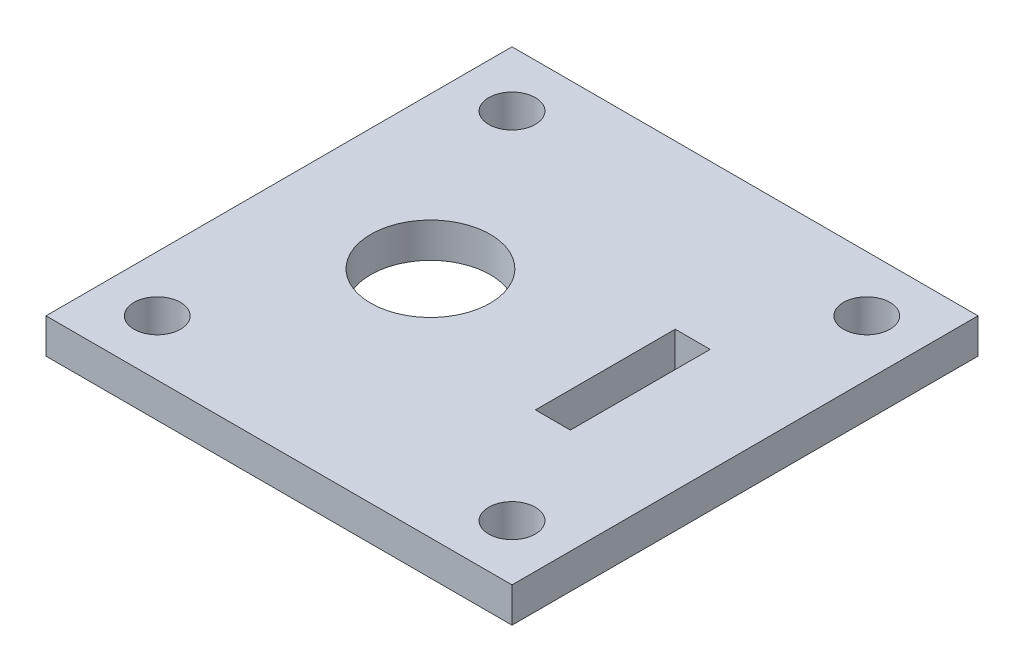
SolidWorks part; units mm, degrees
ref_plane "前视基准面" through (0, 0, 0) normal (0, 0, 1) x (1, 0, 0)
ref_plane "上视基准面" through (0, 0, 0) normal (0, 1, 0) x (1, 0, 0)
ref_plane "右视基准面" through (0, 0, 0) normal (1, 0, 0) x (0, 0, -1)
sketch "草图2" plane through (0, 0, 0) normal (0, 1, 0) x (1, 0, 0)
  line L0 (0, 0) -> (31.047, 0) construction
  line L1 (-9.75, -9.75) -> (9.75, -9.75)
  line L2 (-9.75, -9.75) -> (-9.75, 9.75)
  line L3 (-9.75, 9.75) -> (9.75, 9.75)
  line L4 (9.75, -9.75) -> (9.75, 9.75)
  line L5 (-9.75, -9.75) -> (9.75, 9.75) construction
  line L6 (-9.75, 9.75) -> (9.75, -9.75) construction
  line L7 (-20, -20) -> (20, -20)
  line L8 (-20, -20) -> (-20, 20)
  line L9 (-20, 20) -> (20, 20)
  line L10 (20, -20) -> (20, 20)
  line L11 (-20, -20) -> (20, 20) construction
  line L12 (-20, 20) -> (20, -20) construction
  line L13 (0, 0) -> (0, 17.7315) construction
  circle A0 centre (15.2248, 15.2248) radius 2
  circle A1 centre (-15.2248, -15.2248) radius 2
  circle A2 centre (15.2248, -15.2248) radius 2
  circle A3 centre (-15.2248, 15.2248) radius 2
  point P0 (0, 0)
  point P6 (0, 0)
  dimension "D5" = 4
  dimension "D1" = 19.5
  dimension "D2" = 19.5
  dimension "D3" = 40
  dimension "D4" = 40
  dimension "D6" = 21.5311
extrude "凸台-拉伸2" add sketch "草图2" along normal blind 3 contours L8 L9 L10 L7
sketch "草图3" plane through (0, 0, 0) normal (0, 1, 0) x (1, 0, 0)
  line L7 (8, 6.0116) -> (11, 6.0116)
  line L8 (8, 6.0116) -> (8, -5.9884)
  line L9 (8, -5.9884) -> (11, -5.9884)
  line L10 (11, 6.0116) -> (11, -5.9884)
  circle A0 centre (-15.2248, -15.2248) radius 2 construction
  circle A1 centre (15.2248, -15.2248) radius 2 construction
  circle A2 centre (15.2248, 15.2248) radius 2 construction
  circle A3 centre (-15.2248, 15.2248) radius 2 construction
  circle A4 centre (-15.2248, -15.2248) radius 2
  circle A5 centre (15.2248, -15.2248) radius 2
  circle A6 centre (15.2248, 15.2248) radius 2
  circle A7 centre (-15.2248, 15.2248) radius 2
  circle A8 centre (-7, 0) radius 5.125
  point P27 (8, 0.0116)
  dimension "D1" = 10.25
  dimension "D2" = 8
  dimension "D5" = 12
  dimension "D6" = 3
extrude "切除-拉伸1" cut sketch "草图3" along normal blind 3
sketch "草图4" plane through (0, 0, 0) normal (0, 1, 0) x (1, 0, 0)
  line L0 (0, 0) -> (31.047, 0) construction
  circle A0 centre (3, 0) radius 2
  dimension "D1" = 4
  dimension "D2" = 3
sketch "草图9" plane through (0, 3, 0) normal (0, 1, 0) x (1, 0, 0)
  line L1 (20, -20) -> (-20, -20)
  line L2 (20, -20) -> (20, 20)
  line L3 (20, 20) -> (-20, 20)
  line L4 (-20, -20) -> (-20, 20)
sketch "草图12" plane through (0, 3, 0) normal (0, 1, 0) x (1, 0, 0)
  circle A0 centre (-7, 0) radius 5.125 construction
  circle A1 centre (-7, 0) radius 5.125
sketch "草图16" plane through (0, 0, 0) normal (1, 0, 0) x (0, 0, -1)
  circle A0 centre (-4.3167, -2.2841) radius 0.8937
  circle A1 centre (-0.9811, -2.2841) radius 0.8937
  circle A2 centre (1.6678, -2.2841) radius 0.8937
  circle A3 centre (4.611, -2.2841) radius 0.8937
